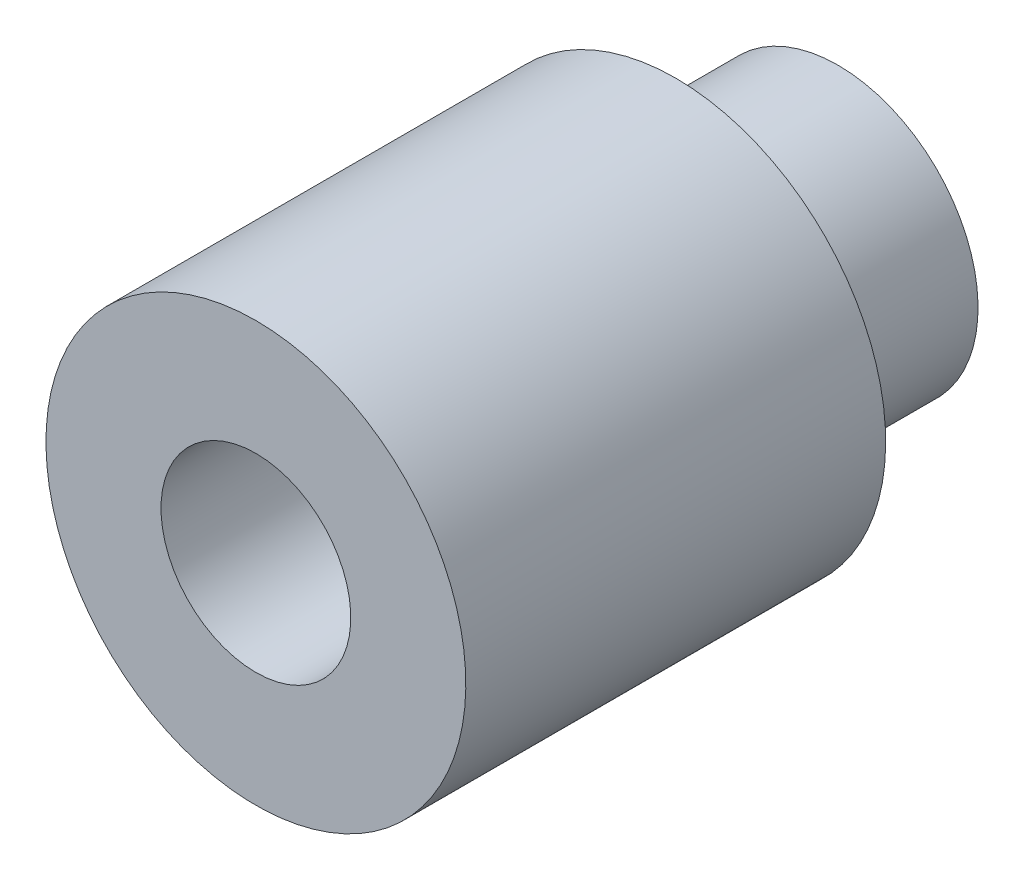
SolidWorks part; units mm, degrees
material "6061-T6 (SS)"
ref_plane "Front Plane" through (0, 0, 0) normal (0, 0, 1) x (1, 0, 0)
ref_plane "Top Plane" through (0, 0, 0) normal (0, 1, 0) x (1, 0, 0)
ref_plane "Right Plane" through (0, 0, 0) normal (1, 0, 0) x (0, 0, -1)
sketch "Sketch1" plane through (0, 0, 0) normal (1, 0, 0) x (0, 0, -1)
  line L0 (0, 0) -> (-9778.9603, 0) construction
  line L1 (0, 2.1526) -> (13.208, 2.1526)
  line L2 (0, 2.1526) -> (0, 4.7625)
  line L3 (0, 4.7625) -> (9.525, 4.7625)
  line L4 (9.525, 3.175) -> (9.525, 4.7625)
  line L7 (9.525, 3.175) -> (13.208, 3.175)
  line L8 (13.208, 2.1526) -> (13.208, 3.175)
  dimension "D1" = 3.683
  dimension "D2" = 6.35
  dimension "D3" = 9.525
  dimension "D4" = 4.3053
  dimension "D5" = 9.525
revolve "Revolve1" add sketch "Sketch1" angle 360 about L0
equation "\"D1@Sketch1\"=.125 + .02"
